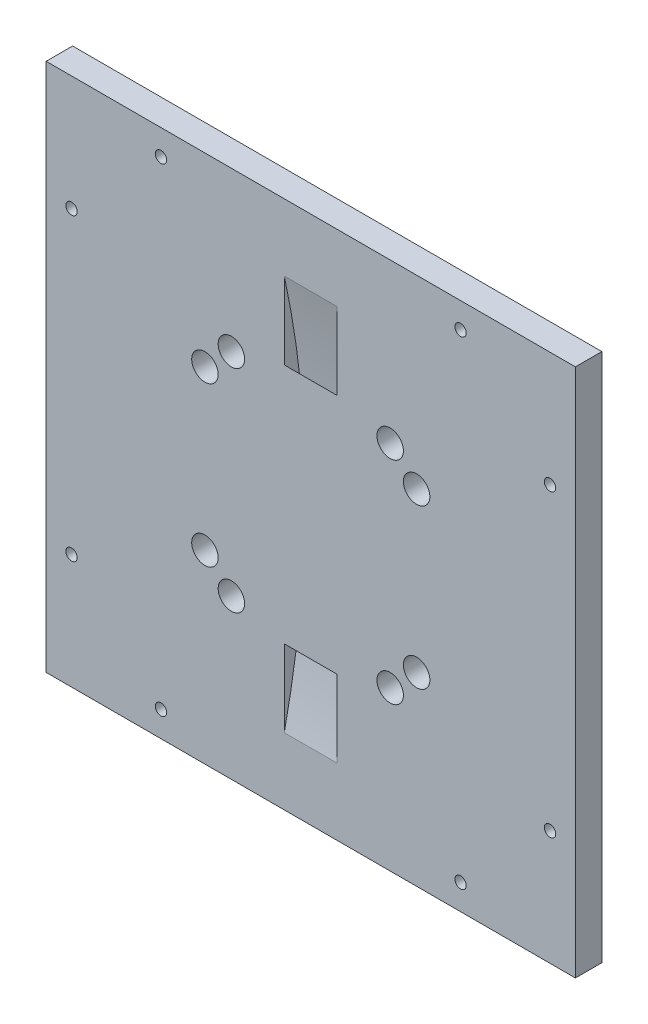
SolidWorks part; units mm, degrees
ref_plane "Front Plane" through (0, 0, 0) normal (0, 0, 1) x (1, 0, 0)
ref_plane "Top Plane" through (0, 0, 0) normal (0, 1, 0) x (1, 0, 0)
ref_plane "Right Plane" through (0, 0, 0) normal (1, 0, 0) x (0, 0, -1)
sketch "Sketch1" plane through (0, 0, 0) normal (0, 0, 1) x (1, 0, 0)
  line L1 (-100, 100) -> (100, 100)
  line L2 (-100, 100) -> (-100, -100)
  line L3 (-100, -100) -> (100, -100)
  line L4 (100, 100) -> (100, -100)
  line L5 (-100, 100) -> (100, -100) construction
  line L6 (-100, -100) -> (100, 100) construction
  point P0 (0, 0)
  dimension "D1" = 200
  dimension "D2" = 200
extrude "Boss-Extrude1" add sketch "Sketch1" along normal blind 10
sketch "Sketch2" plane through (0, 0, 10) normal (0, 0, 1) x (1, 0, 0)
  line L1 (-40, 30) -> (40, 30) construction
  line L2 (-40, 30) -> (-40, -30) construction
  line L3 (-40, -30) -> (40, -30) construction
  line L4 (40, 30) -> (40, -30) construction
  line L5 (-40, 30) -> (40, -30) construction
  line L6 (-40, -30) -> (40, 30) construction
  line L7 (30, 40) -> (-30, 40) construction
  line L8 (30, 40) -> (30, -40) construction
  line L9 (30, -40) -> (-30, -40) construction
  line L10 (-30, 40) -> (-30, -40) construction
  line L11 (30, 40) -> (-30, -40) construction
  line L12 (30, -40) -> (-30, 40) construction
  line L13 (-90.4, 56.6) -> (90.4, 56.6) construction
  line L14 (-90.4, 56.6) -> (-90.4, -56.6) construction
  line L15 (-90.4, -56.6) -> (90.4, -56.6) construction
  line L16 (90.4, 56.6) -> (90.4, -56.6) construction
  line L17 (-90.4, 56.6) -> (90.4, -56.6) construction
  line L18 (-90.4, -56.6) -> (90.4, 56.6) construction
  line L19 (-56.6, 90.4) -> (56.6, 90.4) construction
  line L20 (-56.6, 90.4) -> (-56.6, -90.4) construction
  line L21 (-56.6, -90.4) -> (56.6, -90.4) construction
  line L22 (56.6, 90.4) -> (56.6, -90.4) construction
  line L23 (-56.6, 90.4) -> (56.6, -90.4) construction
  line L24 (-56.6, -90.4) -> (56.6, 90.4) construction
  circle A0 centre (-40, 30) radius 5
  circle A1 centre (40, 30) radius 5
  circle A2 centre (40, -30) radius 5
  circle A3 centre (-40, -30) radius 5
  circle A4 centre (-30, 40) radius 5
  circle A5 centre (30, 40) radius 5
  circle A6 centre (30, -40) radius 5
  circle A7 centre (-30, -40) radius 5
  circle A8 centre (-56.6, 90.4) radius 2.15
  circle A9 centre (-90.4, 56.6) radius 2.15
  circle A10 centre (-90.4, -56.6) radius 2.15
  circle A11 centre (-56.6, -90.4) radius 2.15
  circle A12 centre (56.6, -90.4) radius 2.15
  circle A13 centre (90.4, -56.6) radius 2.15
  circle A14 centre (90.4, 56.6) radius 2.15
  circle A15 centre (56.6, 90.4) radius 2.15
  point P0 (0, 0)
  point P10 (0, 0)
  point P19 (0, 0)
  point P24 (0, 0)
  dimension "D3" = 10
  dimension "D4" = 113.2
  dimension "D6" = 4.3
  dimension "D1" = 60
  dimension "D2" = 80
  dimension "D5" = 180.8
extrude "Cut-Extrude1" cut sketch "Sketch2" against normal through all
sketch "Sketch3" plane through (0, 0, 0) normal (0, 1, 0) x (1, 0, 0)
  line L0 (0, -4.4923) -> (0, -354.4923) construction
  line L1 (-10, -6.9923) -> (10, -6.9923)
  line L2 (-10, -6.9923) -> (-10, -1.9923)
  line L3 (-10, -1.9923) -> (10, -1.9923)
  line L4 (10, -6.9923) -> (10, -1.9923)
  line L5 (-10, -6.9923) -> (10, -1.9923) construction
  line L6 (-10, -1.9923) -> (10, -6.9923) construction
  line L7 (0, -354.4923) -> (23.0759, -354.4923) construction
  point P0 (0, -4.4923)
  dimension "D1" = 350
  dimension "D2" = 20
  dimension "D3" = 5
revolve "Cut-Revolve1" cut sketch "Sketch3" angle 360 about L7
